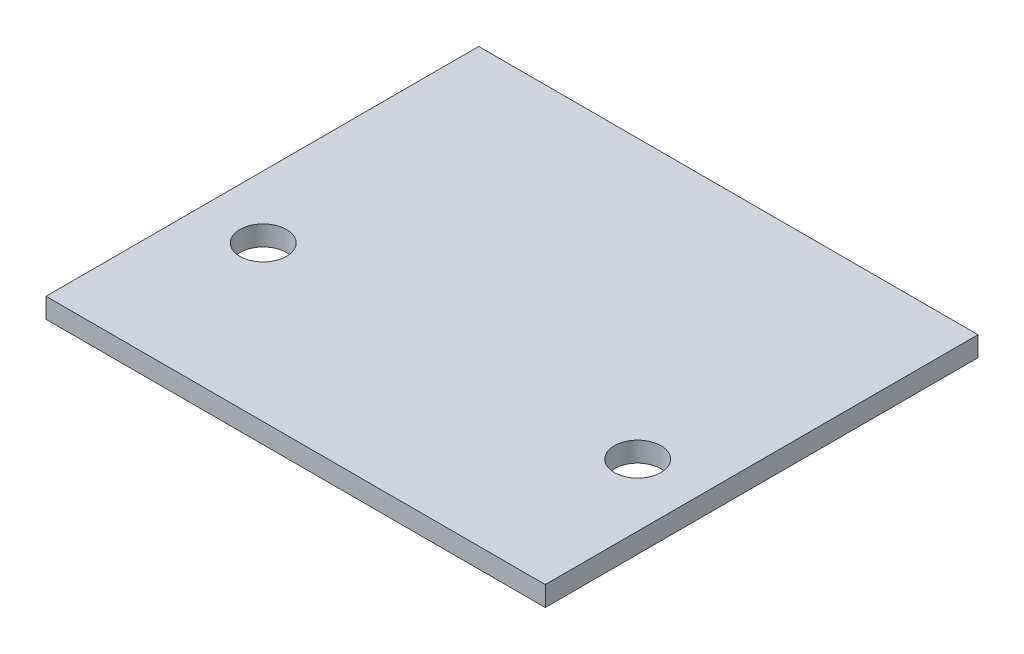
SolidWorks part; units mm, degrees
ref_plane "前视基准面" through (0, 0, 0) normal (0, 0, 1) x (1, 0, 0)
ref_plane "上视基准面" through (0, 0, 0) normal (0, 1, 0) x (1, 0, 0)
ref_plane "右视基准面" through (0, 0, 0) normal (1, 0, 0) x (0, 0, -1)
other "Configuration Table"
sketch "草图1" plane through (0, 0, 0) normal (0, 1, 0) x (1, 0, 0)
  line L0 (0, 22.2837) -> (0, -18.7813) construction
  line L1 (-15, -13) -> (15, -13)
  line L2 (-15, -13) -> (-15, 13)
  line L3 (-15, 13) -> (15, 13)
  line L4 (15, -13) -> (15, 13)
  line L5 (-15, -13) -> (15, 13) construction
  line L6 (-15, 13) -> (15, -13) construction
  circle A0 centre (-11.25, -3.7) radius 1.4
  circle A1 centre (11.25, -3.7) radius 1.4
  point P0 (0, 0)
  dimension "D3" = 22.5
  dimension "D4" = 2.8
  dimension "D5" = 9.3
  dimension "D1" = 30
  dimension "D2" = 26
extrude "凸台-拉伸1" add sketch "草图1" along normal blind 1.2
